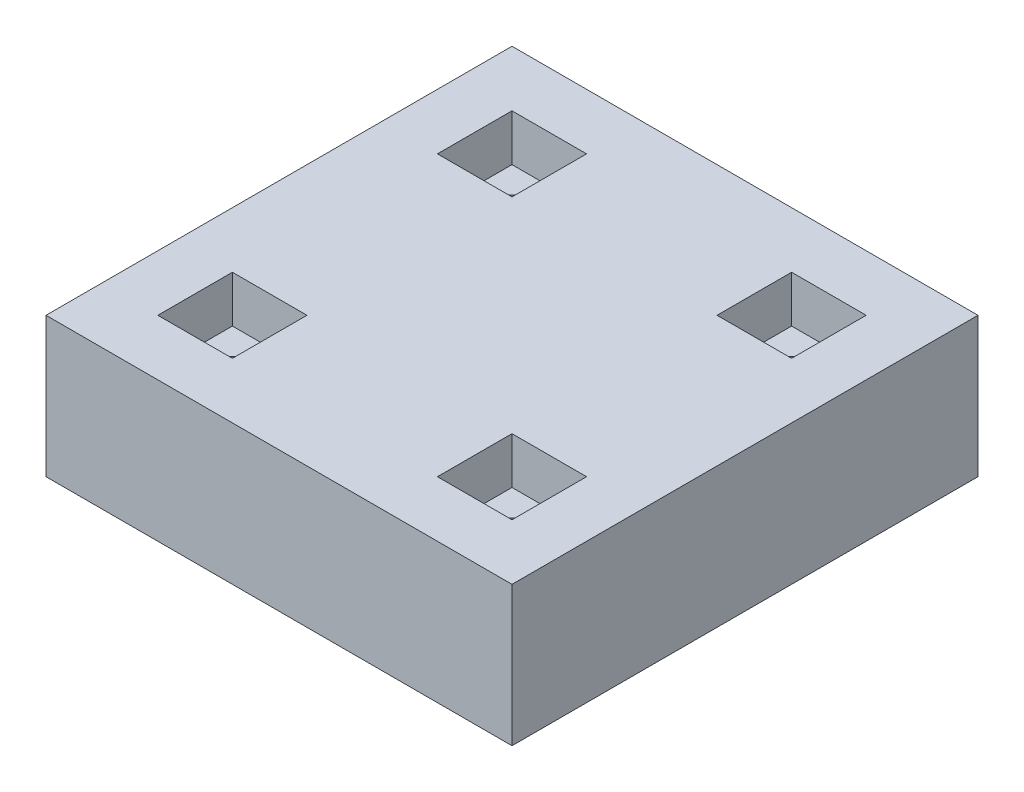
SolidWorks part; units mm, degrees
ref_plane "Front Plane" through (0, 0, 0) normal (0, 0, 1) x (1, 0, 0)
ref_plane "Top Plane" through (0, 0, 0) normal (0, 1, 0) x (1, 0, 0)
ref_plane "Right Plane" through (0, 0, 0) normal (1, 0, 0) x (0, 0, -1)
sketch "Sketch1" plane through (0, 0, 0) normal (0, 1, 0) x (1, 0, 0)
  line L1 (25, 25) -> (-25, 25)
  line L2 (25, 25) -> (25, -25)
  line L3 (25, -25) -> (-25, -25)
  line L4 (-25, 25) -> (-25, -25)
  line L5 (25, 25) -> (-25, -25) construction
  line L6 (25, -25) -> (-25, 25) construction
  point P0 (0, 0)
  dimension "D1" = 50
  dimension "D2" = 50
extrude "Boss-Extrude1" add sketch "Sketch1" along normal blind 15
sketch "Sketch2" plane through (0, 15, 0) normal (0, 1, 0) x (1, 0, 0)
  line L0 (0, 46.4469) -> (0, -54.0545) construction
  line L2 (120, 60) -> (-120, 60) construction
  line L3 (120, 60) -> (120, -60) construction
  line L4 (120, -60) -> (-120, -60) construction
  line L5 (-120, 60) -> (-120, -60) construction
  line L6 (120, 60) -> (-120, -60) construction
  line L7 (120, -60) -> (-120, 60) construction
  line L8 (-82.3505, 0) -> (95.8521, 0) construction
  circle A0 centre (0, 23) radius 2
  circle A1 centre (-60, 23) radius 2
  circle A2 centre (60, 23) radius 2
  circle A3 centre (60, -23) radius 2
  circle A4 centre (0, -23) radius 2
  circle A5 centre (-60, -23) radius 2
  point P5 (0, 0)
  dimension "D1" = 240
  dimension "D4" = 60
  dimension "D5" = 60
  dimension "D2" = 120
  dimension "D3" = 23
sketch "Sketch3" plane through (0, 15, 0) normal (0, 1, 0) x (1, 0, 0)
  line L0 (-1000, 0) -> (49000, 0) construction
  line L1 (0, -1000) -> (0, 49000) construction
  line L2 (25, 25) -> (-25, 25) construction
  line L3 (-25, 25) -> (-25, -25) construction
  line L4 (19, 19) -> (11, 19)
  line L5 (-19, 11) -> (-11, 11)
  line L6 (-19, 11) -> (-19, 19)
  line L7 (-19, 19) -> (-11, 19)
  line L8 (-11, 11) -> (-11, 19)
  line L9 (-19, 11) -> (-11, 19) construction
  line L10 (-19, 19) -> (-11, 11) construction
  line L11 (11, 11) -> (11, 19)
  line L12 (19, 11) -> (11, 11)
  line L13 (19, 11) -> (19, 19)
  line L14 (-19, -19) -> (-11, -19)
  line L15 (-11, -11) -> (-11, -19)
  line L16 (-19, -11) -> (-11, -11)
  line L17 (-19, -11) -> (-19, -19)
  line L18 (19, -11) -> (19, -19)
  line L19 (19, -11) -> (11, -11)
  line L20 (11, -11) -> (11, -19)
  line L21 (19, -19) -> (11, -19)
  point P4 (-15, 15)
  point P11 (15, 15)
  point P13 (-15, -15)
  point P14 (15, -15)
  point P15 (-15, 15)
  dimension "D1" = 10
  dimension "D2" = 10
  dimension "D3" = 8
  dimension "D4" = 8
hole_wizard "Tap Drill for M4x0.7 Tap1" positions "Sketch4" profile "Sketch6" hole size "M4x0.7" standard "ANSI Metric" end condition through all
sketch "Sketch4" plane through (0, 15, 0) normal (0, 1, 0) x (1, 0, 0)
  point P0 (-15, 15)
  point P3 (15, 15)
  point P6 (15, -15)
  point P9 (-15, -15)
sketch "Sketch6" plane through (-15, 15, -15) normal (1, 0, 0) x (0, 0, 1)
  line L0 (0, 0) -> (0, 15)
  line L1 (0, 15) -> (1.65, 15)
  line L2 (1.65, 15) -> (1.65, 0.025)
  line L3 (1.65, 0.025) -> (1.675, 0)
  line L5 (1.675, 0) -> (0, 0)
  line L6 (-1.65, 0.025) -> (-1.675, 0) construction
  line L11 (0, -6.35) -> (0, 107.95) construction
  dimension "Thru Hole Dia." = 3.3
  dimension "Thru Hole Depth" = 15
  dimension "Near C'Sink Dia." = 3.35
  dimension "Near C'Sink Angle" = 90
extrude "Cut-Extrude2" cut sketch "Sketch3" against normal blind 5
